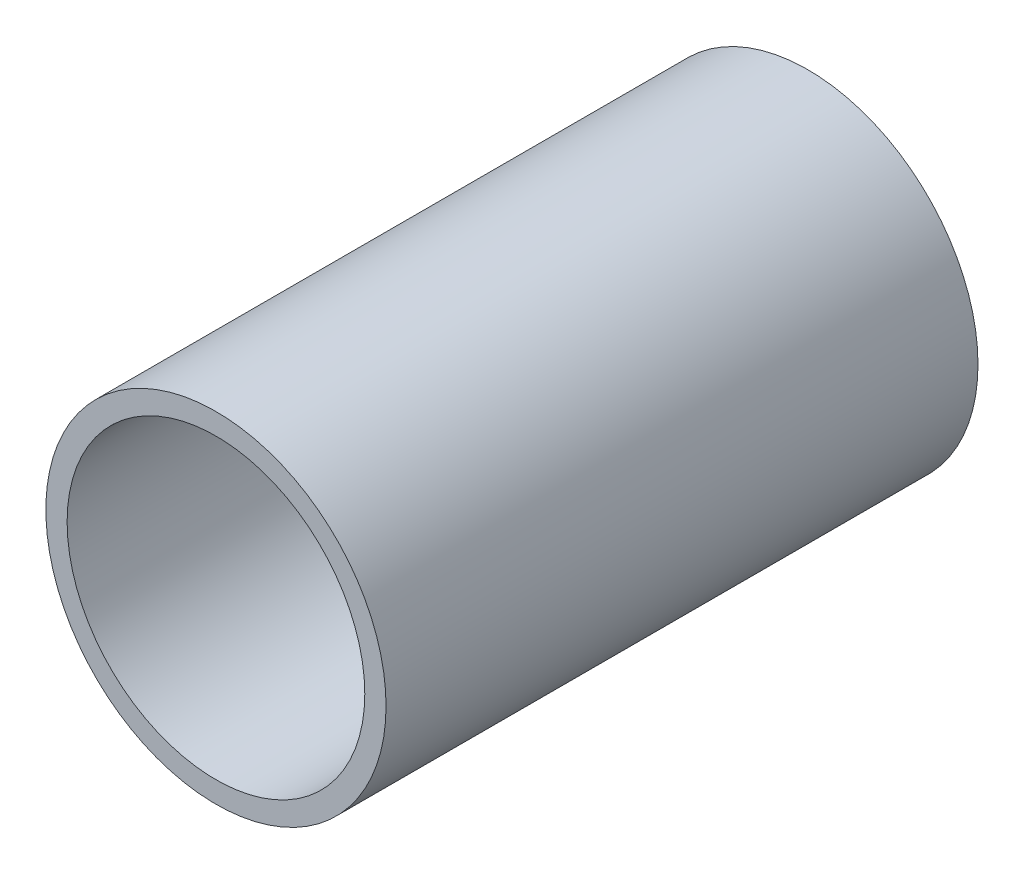
SolidWorks part; units mm, degrees
ref_plane "Front Plane" through (0, 0, 0) normal (0, 0, 1) x (1, 0, 0)
ref_plane "Top Plane" through (0, 0, 0) normal (0, 1, 0) x (1, 0, 0)
ref_plane "Right Plane" through (0, 0, 0) normal (1, 0, 0) x (0, 0, -1)
sketch "Sketch1" plane through (0, 0, 0) normal (0, 0, 1) x (1, 0, 0)
  circle A0 centre (0, 0) radius 12.7
  circle A1 centre (0, 0) radius 11.1125
  dimension "D1" = 25.4
  dimension "D2" = 22.225
extrude "Boss-Extrude1" add sketch "Sketch1" along normal blind 44.196
